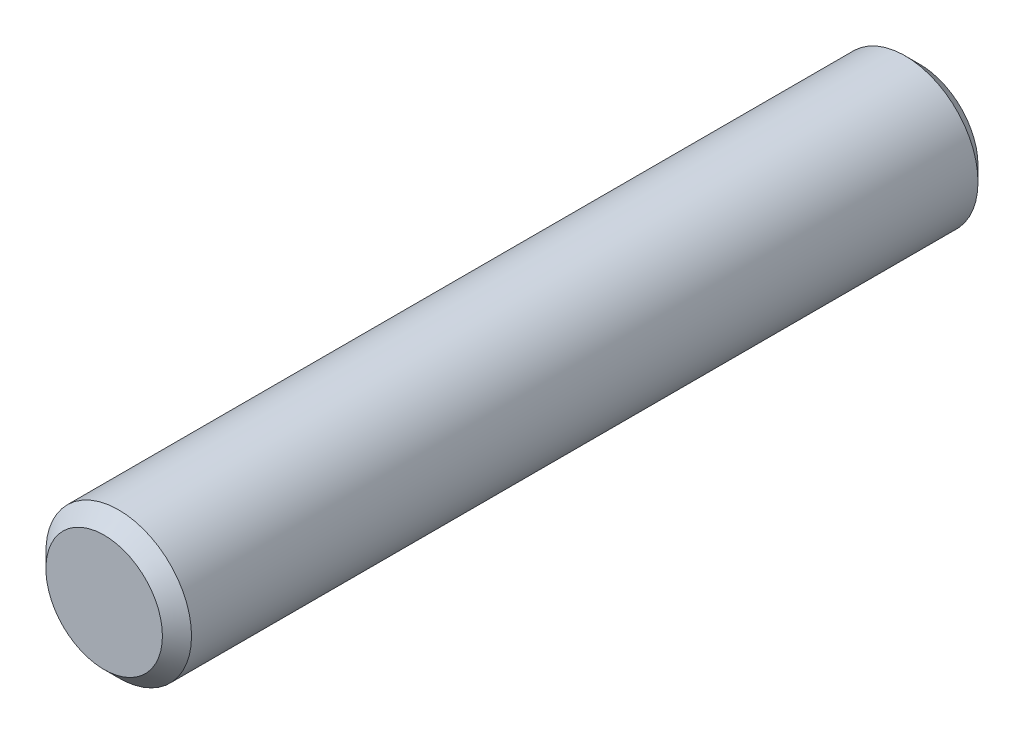
SolidWorks part; units mm, degrees
ref_plane "Front Plane" through (0, 0, 0) normal (0, 0, 1) x (1, 0, 0)
ref_plane "Top Plane" through (0, 0, 0) normal (0, 1, 0) x (1, 0, 0)
ref_plane "Right Plane" through (0, 0, 0) normal (1, 0, 0) x (0, 0, -1)
sketch "Sketch1" plane through (0, 0, 0) normal (0, 0, 1) x (1, 0, 0)
  circle A0 centre (0, 0) radius 2.5
  dimension "D1" = 5
extrude "Boss-Extrude1" add sketch "Sketch1" along normal mid plane 28
chamfer "Chamfer1" distance 0.5 angle 45 2 edges at (2.5, 0, -14) (2.5, 0, 14)
